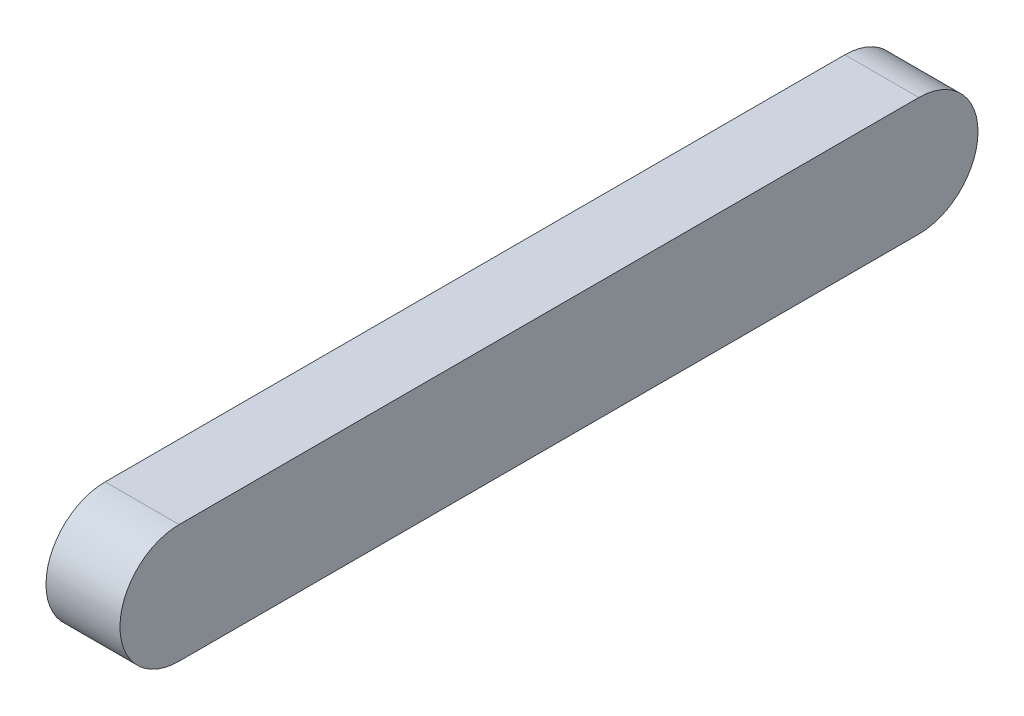
SolidWorks part; units mm, degrees
ref_plane "Front Plane" through (0, 0, 0) normal (0, 0, 1) x (1, 0, 0)
ref_plane "Top Plane" through (0, 0, 0) normal (0, 1, 0) x (1, 0, 0)
ref_plane "Right Plane" through (0, 0, 0) normal (1, 0, 0) x (0, 0, -1)
sketch "Sketch1" plane through (0, 0, 0) normal (1, 0, 0) x (0, 0, -1)
  line L0 (-15.875, 0) -> (15.875, 0) construction
  line L1 (-15.875, 2.54) -> (15.875, 2.54)
  line L2 (-15.875, -2.54) -> (15.875, -2.54)
  arc A0 (-15.875, 2.54) -> (-15.875, -2.54) centre (-15.875, 0) ccw
  arc A1 (15.875, -2.54) -> (15.875, 2.54) centre (15.875, 0) ccw
  point P2 (0, 0)
  dimension "D2" = 2.54
  dimension "D1" = 31.75
extrude "Boss-Extrude1" add sketch "Sketch1" along normal blind 3.175
